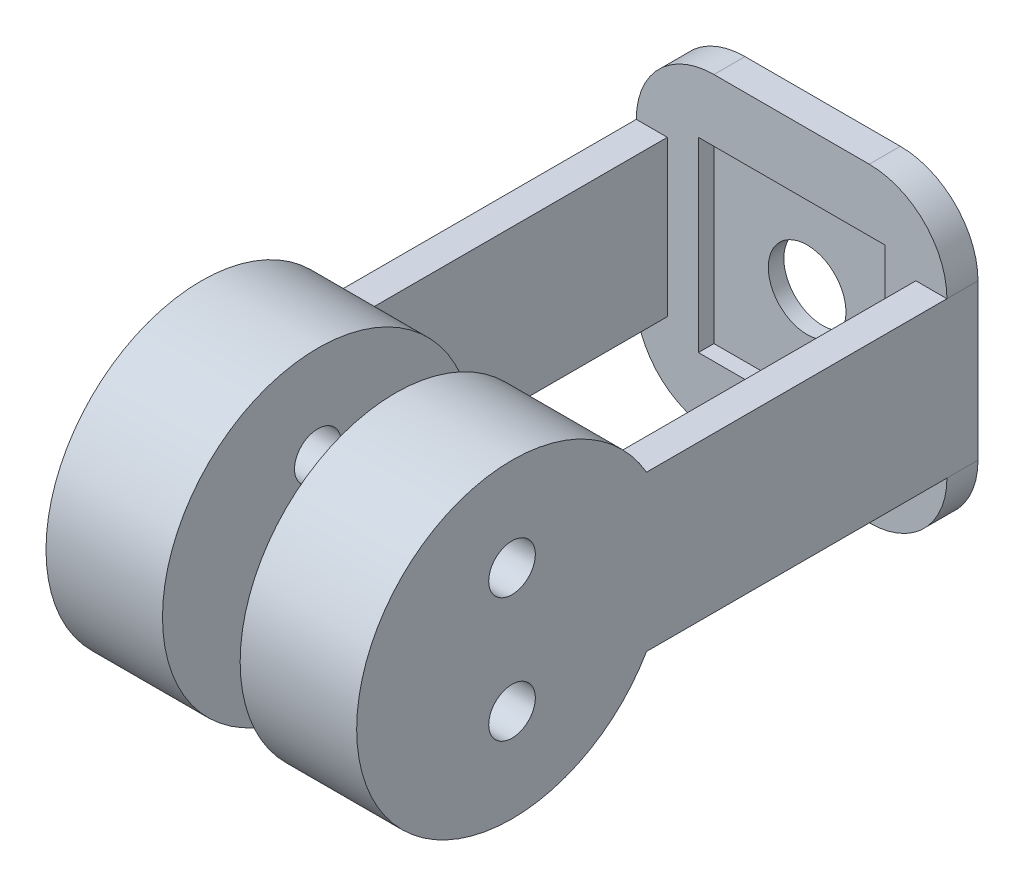
SolidWorks part; units mm, degrees
ref_plane "Front Plane" through (0, 0, 0) normal (0, 0, 1) x (1, 0, 0)
ref_plane "Top Plane" through (0, 0, 0) normal (0, 1, 0) x (1, 0, 0)
ref_plane "Right Plane" through (0, 0, 0) normal (1, 0, 0) x (0, 0, -1)
sketch "Sketch1" plane through (0, 0, 0) normal (0, 0, 1) x (1, 0, 0)
  line L1 (-10, 10) -> (10, 10)
  line L2 (-10, 10) -> (-10, -10)
  line L3 (-10, -10) -> (10, -10)
  line L4 (10, 10) -> (10, -10)
  line L5 (-10, 10) -> (10, -10) construction
  line L6 (-10, -10) -> (10, 10) construction
  point P0 (0, 0)
  dimension "D1" = 20
  dimension "D2" = 20
extrude "Boss-Extrude1" add sketch "Sketch1" along normal blind 2
sketch "Sketch3" plane through (0, 0, 0) normal (0, 0, -1) x (-1, 0, 0)
  circle A0 centre (0, 0) radius 2.5
  dimension "D1" = 5
extrude "Cut-Extrude1" cut sketch "Sketch3" against normal through all
sketch "Sketch4" plane through (0, 0, 2) normal (0, 0, 1) x (1, 0, 0)
  line L1 (-6, 6) -> (6, 6)
  line L2 (-6, 6) -> (-6, -6)
  line L3 (-6, -6) -> (6, -6)
  line L4 (6, 6) -> (6, -6)
  line L5 (-6, 6) -> (6, -6) construction
  line L6 (-6, -6) -> (6, 6) construction
  point P0 (0, 0)
  dimension "D1" = 12
  dimension "D2" = 12
extrude "Cut-Extrude2" cut sketch "Sketch4" against normal blind 1
sketch "Sketch5" plane through (0, 0, 2) normal (0, 0, 1) x (1, 0, 0)
  line L0 (-10, -10) -> (10, -10) construction
  line L1 (10, 10) -> (8, 10)
  line L2 (10, 10) -> (10, -10)
  line L3 (10, -10) -> (8, -10)
  line L4 (8, 10) -> (8, -10)
  line L6 (-10, 10) -> (-8, 10)
  line L7 (-10, 10) -> (-10, -10)
  line L8 (-10, -10) -> (-8, -10)
  line L9 (-8, 10) -> (-8, -10)
  dimension "D1" = 2
  dimension "D2" = 2
extrude "Boss-Extrude2" add sketch "Sketch5" along normal blind 38
sketch "Sketch6" plane through (-10, 0, 0) normal (-1, 0, 0) x (0, 0, 1)
  line L0 (40, 10) -> (40, -10) construction
  line L1 (30, 10) -> (40, 10)
  line L2 (40, 10) -> (40, -10)
  line L3 (40, -10) -> (0, -10) construction
  line L4 (40, -10) -> (30, -10)
  arc A0 (30, -10) -> (30, 10) centre (30, 0) ccw
  point P0 (30, 0)
  line M2 (0, -10) -> (40, -10)
  line M3 (40, -10) -> (40, 10)
  line M4 (40, 10) -> (0, 10)
  dimension "D1" = 10
extrude "Cut-Extrude3" cut sketch "Sketch6" against normal through all contours A0 L2 M4 | A0 M2 M3
sketch "Sketch7" plane through (-10, 0, 0) normal (-1, 0, 0) x (0, 0, 1)
  circle A0 centre (30, 0) radius 10
extrude "Boss-Extrude3" add sketch "Sketch7" against normal blind 7.5
sketch "Sketch8" plane through (10, 0, 0) normal (1, 0, 0) x (0, 0, -1)
  circle A0 centre (-30, 0) radius 10
extrude "Boss-Extrude4" add sketch "Sketch8" against normal blind 7.5
sketch "Sketch9" plane through (-10, 0, 0) normal (-1, 0, 0) x (0, 0, 1)
  line L0 (30, 10) -> (30, -10)
  circle A0 centre (30, 4) radius 1.5
  circle A1 centre (30, -4) radius 1.5
  point P4 (30, 0)
  point P5 (30, 4)
  point P6 (30, -4)
  dimension "D3" = 3
  dimension "D4" = 3
  dimension "D1" = 4
  dimension "D2" = 4
extrude "Cut-Extrude4" cut sketch "Sketch9" against normal through all contours L0 A0 | L0 A0 | L0 A1 | L0 A1
sketch "Sketch11" plane through (10, 0, 0) normal (1, 0, 0) x (0, 0, -1)
  line L0 (-2, -10) -> (-30, -10)
  line L1 (-30, 10) -> (0, 10) construction
  line L2 (0, -10) -> (-2, -10)
  line L3 (0, -10) -> (0, 10)
  line L4 (0, 10) -> (-2, 10)
  line L5 (-2, -10) -> (-2, 10)
  line L6 (-2, -5) -> (-21.3397, -5)
  line L7 (-2, 5) -> (-21.3397, 5)
  line L8 (-2, 10) -> (-30, 10)
  circle A0 centre (-30, 0) radius 10
  point P13 (-2, 0)
  point P14 (-2, -5)
  point P15 (-2, 5)
  line M5 (0, 10) -> (-30, 10)
  line M7 (-30, -10) -> (0, -10)
  dimension "D1" = 2
  dimension "D2" = 5
  dimension "D3" = 5
extrude "Cut-Extrude5" cut sketch "Sketch11" against normal through all contours A0 L5 L6 M7 | A0 L7 L5 M5
fillet "Fillet1" radius 5 2 edges at (-10, 10, 1) (-10, 7.5, 2)
fillet "Fillet2" radius 5 2 edges at (10, 10, 1) (10, 7.5, 2)
fillet "Fillet3" radius 5 2 edges at (10, -10, 1) (10, -7.5, 2)
fillet "Fillet4" radius 5 2 edges at (-10, -10, 1) (-10, -7.5, 2)
